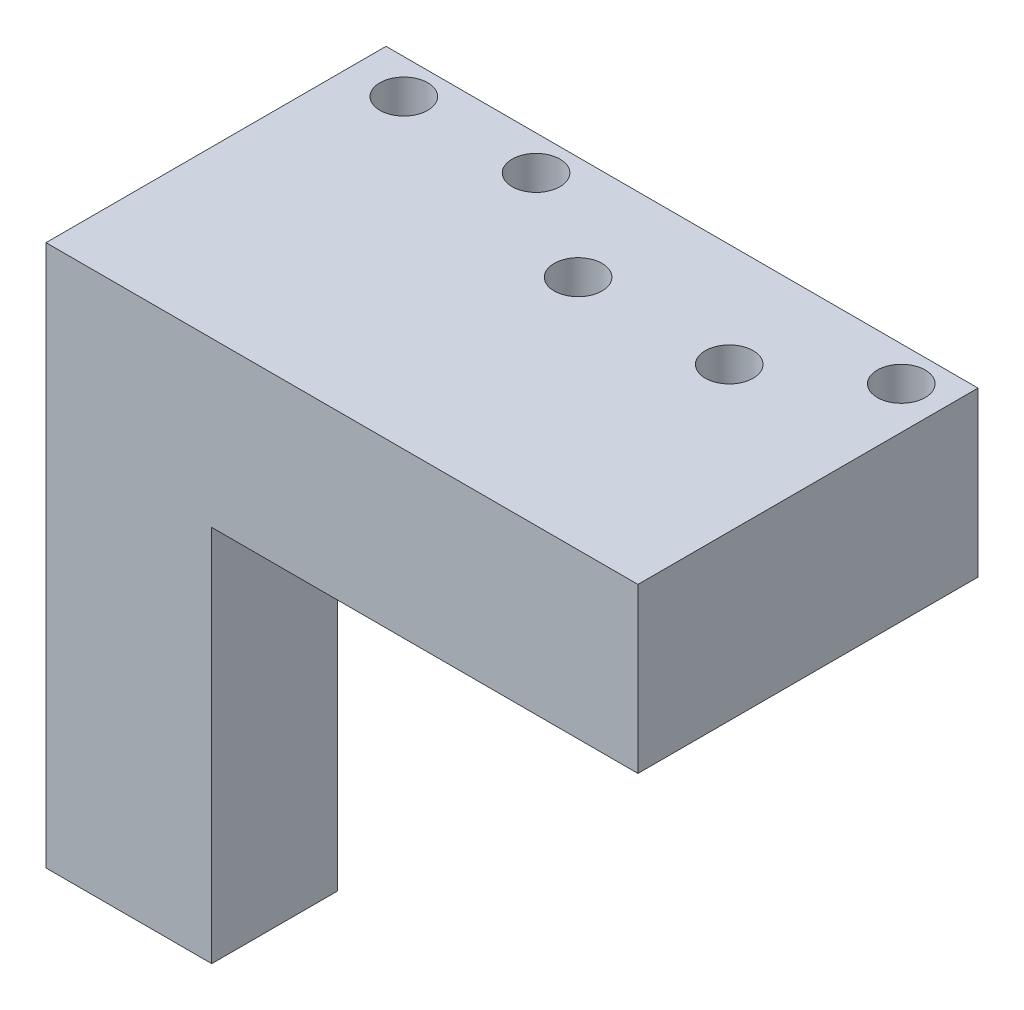
SolidWorks part; units mm, degrees
ref_plane "前视基准面" through (0, 0, 0) normal (0, 0, 1) x (1, 0, 0)
ref_plane "上视基准面" through (0, 0, 0) normal (0, 1, 0) x (1, 0, 0)
ref_plane "右视基准面" through (0, 0, 0) normal (1, 0, 0) x (0, 0, -1)
other "Configuration Table"
sketch "草图1" plane through (0, 0, 0) normal (0, 1, 0) x (1, 0, 0)
  line L0 (-23.5, -5.5) -> (-23.5, -21.5)
  line L1 (-23.5, 5.5) -> (23.5, 5.5)
  line L2 (-23.5, 5.5) -> (-23.5, -5.5)
  line L4 (23.5, 5.5) -> (23.5, -5.5)
  line L5 (-23.5, 5.5) -> (23.5, -5.5) construction
  line L6 (-23.5, -5.5) -> (23.5, 5.5) construction
  line L7 (-23.5, -21.5) -> (23.5, -21.5)
  line L8 (23.5, -21.5) -> (23.5, -5.5)
  circle A6 centre (20.1592, 2.75) radius 1.9
  circle A7 centre (-8.8408, 2.75) radius 1.9
  circle A8 centre (-19.3408, 2.75) radius 1.9
  circle A9 centre (0, -2.75) radius 1.9
  circle A10 centre (12, -2.75) radius 1.9
  point P0 (0, 0)
  dimension "D3" = 3.8
  dimension "D4" = 2.75
  dimension "D5" = 3.8
  dimension "D6" = 3.8
  dimension "D1" = 11
  dimension "D2" = 47
  dimension "D7" = 12
  dimension "D8" = 16
extrude "凸台-拉伸1" add sketch "草图1" along normal blind 13
sketch "草图2" plane through (0, 0, 21.5) normal (0, 0, 1) x (1, 0, 0)
  line L0 (-10.3408, 0) -> (-10.3408, -30)
  line L1 (-23.5, 0) -> (-10.3408, 0)
  line L2 (-23.5, 0) -> (-23.5, -30)
  line L3 (-23.5, -30) -> (-10.3408, -30)
  line L5 (-10.3408, 0) -> (-10.3408, -30) construction
extrude "凸台-拉伸2" add sketch "草图2" against normal blind 10
